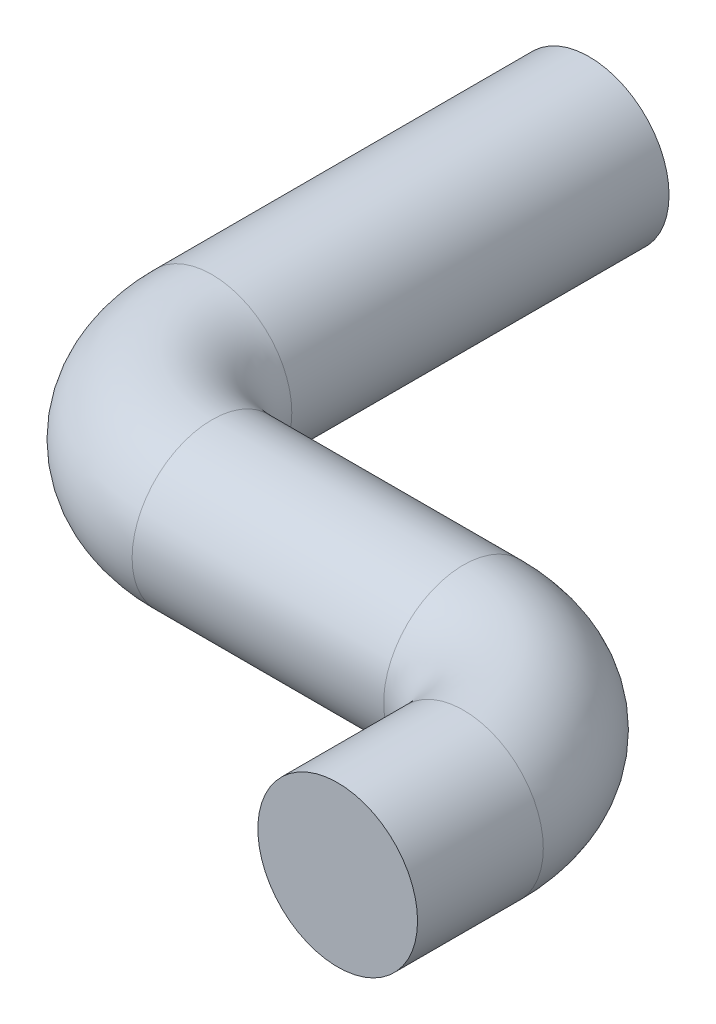
SolidWorks part; units mm, degrees
ref_plane "Alzado" through (0, 0, 0) normal (0, 0, 1) x (1, 0, 0)
ref_plane "Planta" through (0, 0, 0) normal (0, 1, 0) x (1, 0, 0)
ref_plane "Vista lateral" through (0, 0, 0) normal (1, 0, 0) x (0, 0, -1)
sketch "Croquis1" plane through (0, 0, 0) normal (0, 1, 0) x (1, 0, 0)
  line L0 (0, 0) -> (0, -30)
  line L1 (10, -40) -> (30, -40)
  line L2 (40, -50) -> (40, -60)
  arc A0 (30, -40) -> (40, -50) centre (30, -50) cw
  arc A1 (0, -30) -> (10, -40) centre (10, -30) ccw
  point P7 (40, -40)
  point P10 (0, -40)
  dimension "D4" = 10
  dimension "D1" = 40
  dimension "D2" = 40
  dimension "D3" = 20
ref_plane "Plano1" through (0, 0, 0) normal (0, 0, 1) x (1, 0, 0)
sketch "Croquis2" plane through (0, 0, 0) normal (0, 0, 1) x (1, 0, 0)
  circle A0 centre (0, 0) radius 6.35
  dimension "D1" = 12.7
sweep "Barrer1" add profiles "Croquis2" path "Croquis1"
